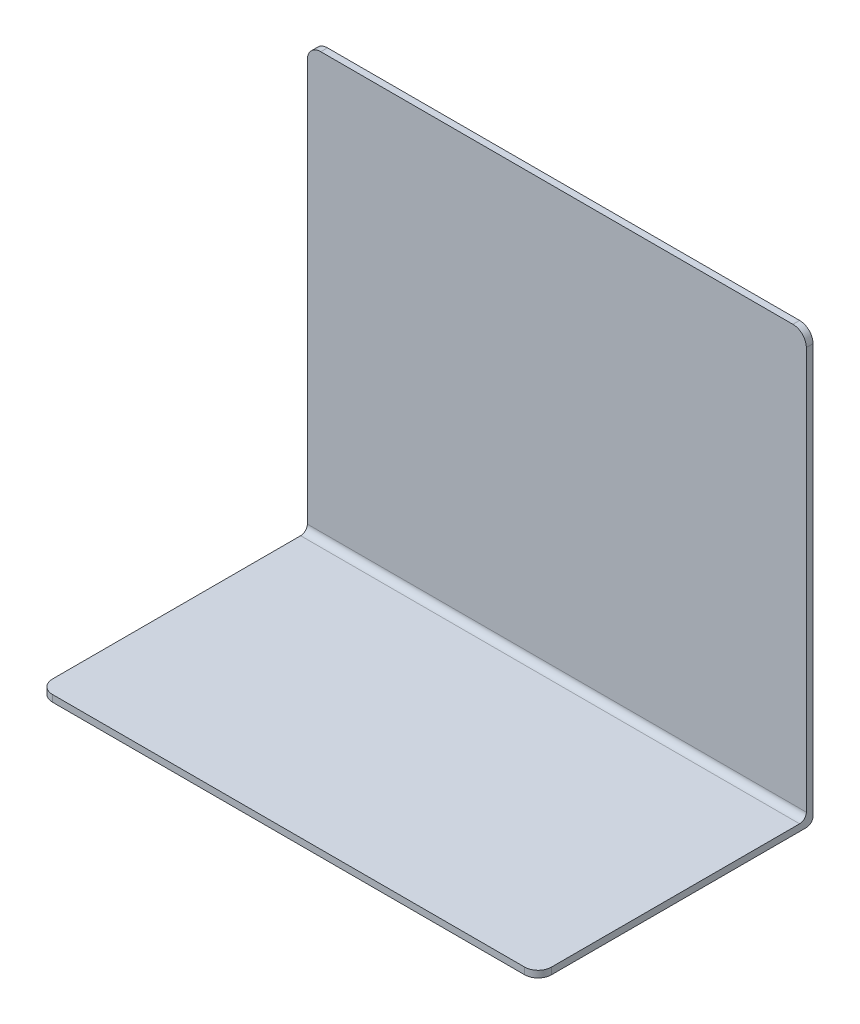
SolidWorks part; units mm, degrees
ref_plane "Front Plane" through (0, 0, 0) normal (0, 0, 1) x (1, 0, 0)
ref_plane "Top Plane" through (0, 0, 0) normal (0, 1, 0) x (1, 0, 0)
ref_plane "Right Plane" through (0, 0, 0) normal (1, 0, 0) x (0, 0, -1)
sketch "Sketch2" plane through (0, 0, 0) normal (0, 0, 1) x (1, 0, 0)
  line L1 (-118.11, -101.6) -> (118.11, -101.6)
  line L2 (-118.11, -101.6) -> (-118.11, 101.6)
  line L3 (-118.11, 101.6) -> (118.11, 101.6)
  line L4 (118.11, -101.6) -> (118.11, 101.6)
  line L5 (-118.11, -101.6) -> (118.11, 101.6) construction
  line L6 (-118.11, 101.6) -> (118.11, -101.6) construction
  point P0 (0, 0)
  dimension "D1" = 236.22
  dimension "D2" = 203.2
extrude "Boss-Extrude1" add sketch "Sketch2" along normal blind 3.175
sketch "Sketch3" plane through (0, 0, 3.175) normal (0, 0, 1) x (1, 0, 0)
  line L0 (118.11, -101.6) -> (118.11, 101.6) construction
  line L1 (-118.11, -101.6) -> (118.11, -101.6)
  line L2 (-118.11, -101.6) -> (-118.11, -98.425)
  line L3 (-118.11, -98.425) -> (118.11, -98.425)
  line L4 (118.11, -101.6) -> (118.11, -98.425)
  dimension "D1" = 3.175
extrude "Boss-Extrude2" add sketch "Sketch3" along normal blind 127
fillet "Fillet1" radius 3.175 2 edges at (0, -101.6, 0) (0, -98.425, 3.175)
fillet "Fillet2" radius 6.35 4 edges at (118.11, -100.0125, 130.175) (-118.11, -100.0125, 130.175) (118.11, 101.6, 1.5875) (-118.11, 101.6, 1.5875)
